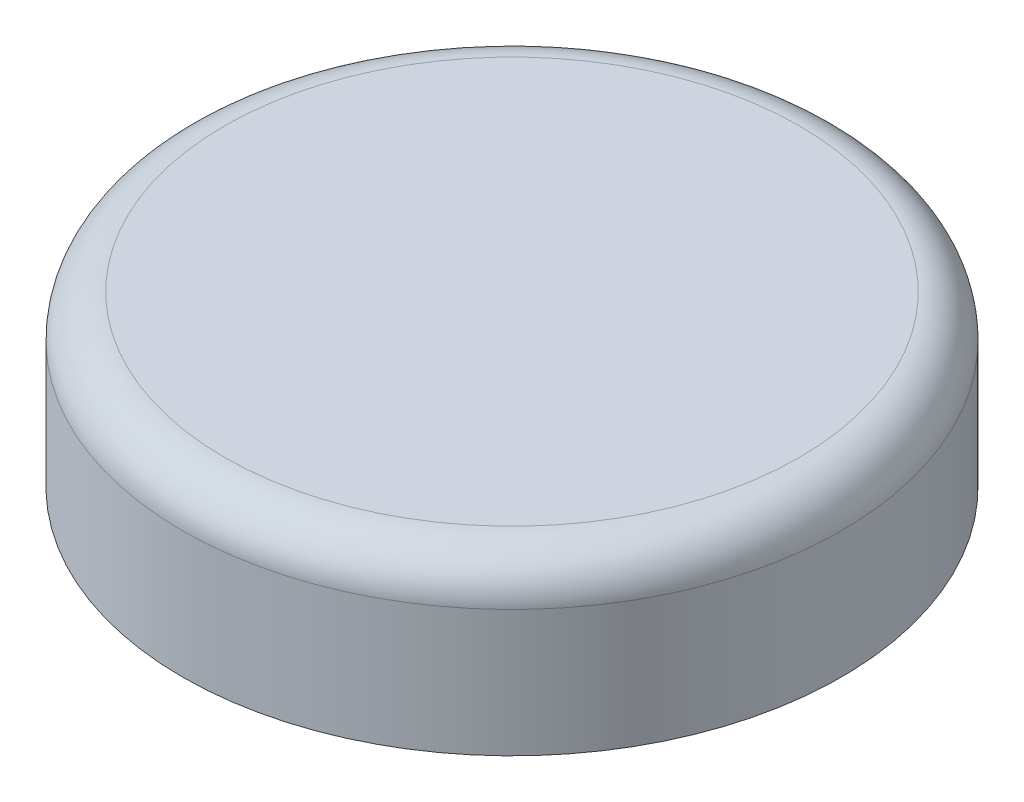
SolidWorks part; units mm, degrees
ref_plane "Front Plane" through (0, 0, 0) normal (0, 0, 1) x (1, 0, 0)
ref_plane "Top Plane" through (0, 0, 0) normal (0, 1, 0) x (1, 0, 0)
ref_plane "Right Plane" through (0, 0, 0) normal (1, 0, 0) x (0, 0, -1)
sketch "Sketch1" plane through (0, 0, 0) normal (0, 1, 0) x (1, 0, 0)
  circle A0 centre (0, 0) radius 3.9
extrude "Boss-Extrude1" add sketch "Sketch1" along normal blind 2
fillet "Fillet1" radius 0.5 1 edges at (0, 2, 3.9)
sketch "Sketch2" plane through (0, 2, 0) normal (0, 1, 0) x (1, 0, 0)
  line L0 (-3.4, 0) -> (3.4, 0) construction
  circle A0 centre (0, 0) radius 3.4 construction
